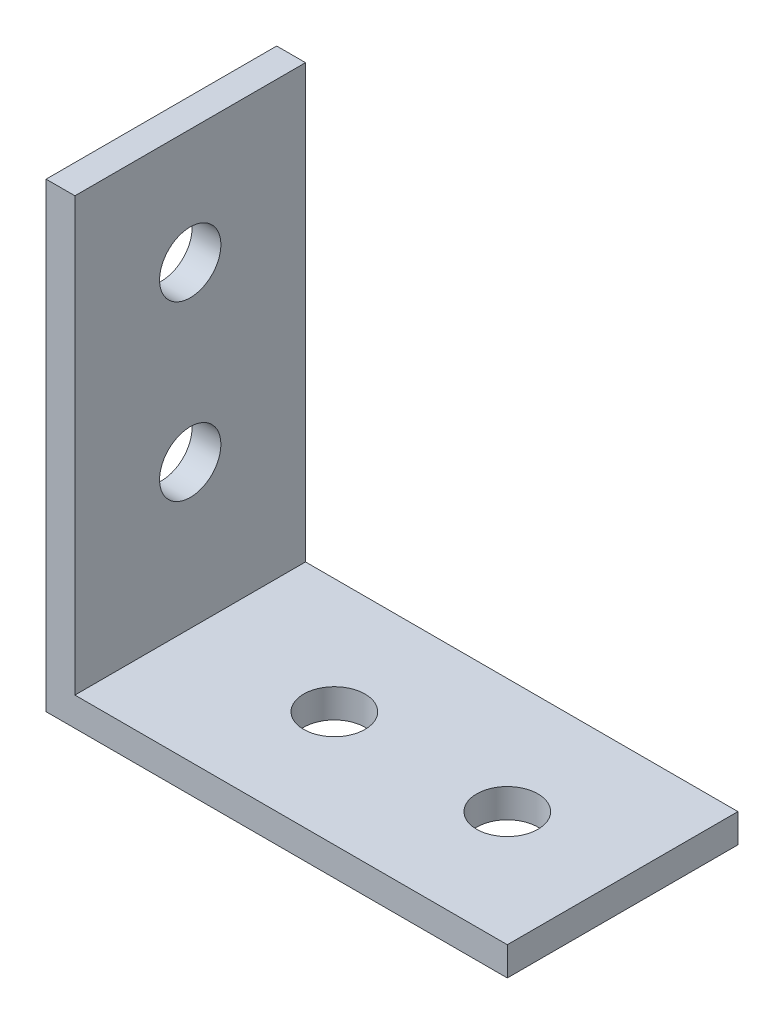
SolidWorks part; units mm, degrees
ref_plane "Front Plane" through (0, 0, 0) normal (0, 0, 1) x (1, 0, 0)
ref_plane "Top Plane" through (0, 0, 0) normal (0, 1, 0) x (1, 0, 0)
ref_plane "Right Plane" through (0, 0, 0) normal (1, 0, 0) x (0, 0, -1)
sketch "Sketch1" plane through (0, 0, 0) normal (0, 0, 1) x (1, 0, 0)
  line L0 (0, 0) -> (0, -50.8)
  line L1 (0, -50.8) -> (50.8, -50.8)
  line L2 (50.8, -50.8) -> (50.8, -47.625)
  line L3 (0, 0) -> (3.175, 0)
  line L4 (3.175, 0) -> (3.175, -47.625)
  line L5 (3.175, -47.625) -> (50.8, -47.625)
  point P3 (50.8, -49.2125)
  dimension "D1" = 3.175
  dimension "D2" = 3.175
  dimension "D3" = 50.8
  dimension "D4" = 50.8
extrude "Boss-Extrude1" add sketch "Sketch1" along normal blind 25.4
hole_wizard "1/4 Clearance Hole1" positions "Sketch3" profile "Sketch2" hole size "1/4" standard "ANSI Inch" end condition up to next
sketch "Sketch3" plane through (0, -47.625, 0) normal (0, 1, 0) x (1, 0, 0)
  line L13 (50.8, 0) -> (3.175, 0) construction
  line L14 (50.8, -25.4) -> (50.8, 0) construction
  point P0 (38.1, -12.7)
  point P57 (19.05, -12.7)
  dimension "D1" = 19.05
  dimension "D2" = 12.7
  dimension "D3" = 12.7
sketch "Sketch2" plane through (38.1, -47.625, 12.7) normal (1, 0, 0) x (0, 0, 1)
  line L0 (0, 0) -> (0, 3.175)
  line L1 (0, 3.175) -> (3.3782, 3.175)
  line L2 (3.3782, 3.175) -> (3.3782, 0)
  line L5 (3.3782, 0) -> (0, 0)
  line L11 (0, -6.35) -> (0, 107.95) construction
  dimension "Thru Hole Dia." = 6.7564
  dimension "Thru Hole Depth" = 3.175
hole_wizard "1/4 Clearance Hole2" positions "Sketch6" profile "Sketch5" hole size "1/4" standard "ANSI Inch" end condition up to next
sketch "Sketch6" plane through (3.175, 0, 0) normal (1, 0, 0) x (0, 0, -1)
  line L6 (-25.4, 0) -> (0, 0) construction
  line L7 (0, -47.625) -> (0, 0) construction
  point P0 (-12.7, -12.7)
  point P29 (-12.7, -31.75)
  dimension "D1" = 19.05
  dimension "D2" = 12.7
  dimension "D4" = 12.7
sketch "Sketch5" plane through (3.175, -12.7, 12.7) normal (0, 1, 0) x (0, 0, -1)
  line L0 (0, 0) -> (0, 3.175)
  line L1 (0, 3.175) -> (3.3782, 3.175)
  line L2 (3.3782, 3.175) -> (3.3782, 0)
  line L5 (3.3782, 0) -> (0, 0)
  line L11 (0, -6.35) -> (0, 107.95) construction
  dimension "Thru Hole Dia." = 6.7564
  dimension "Thru Hole Depth" = 3.175
equation "\".75ibn\"=6.35"
